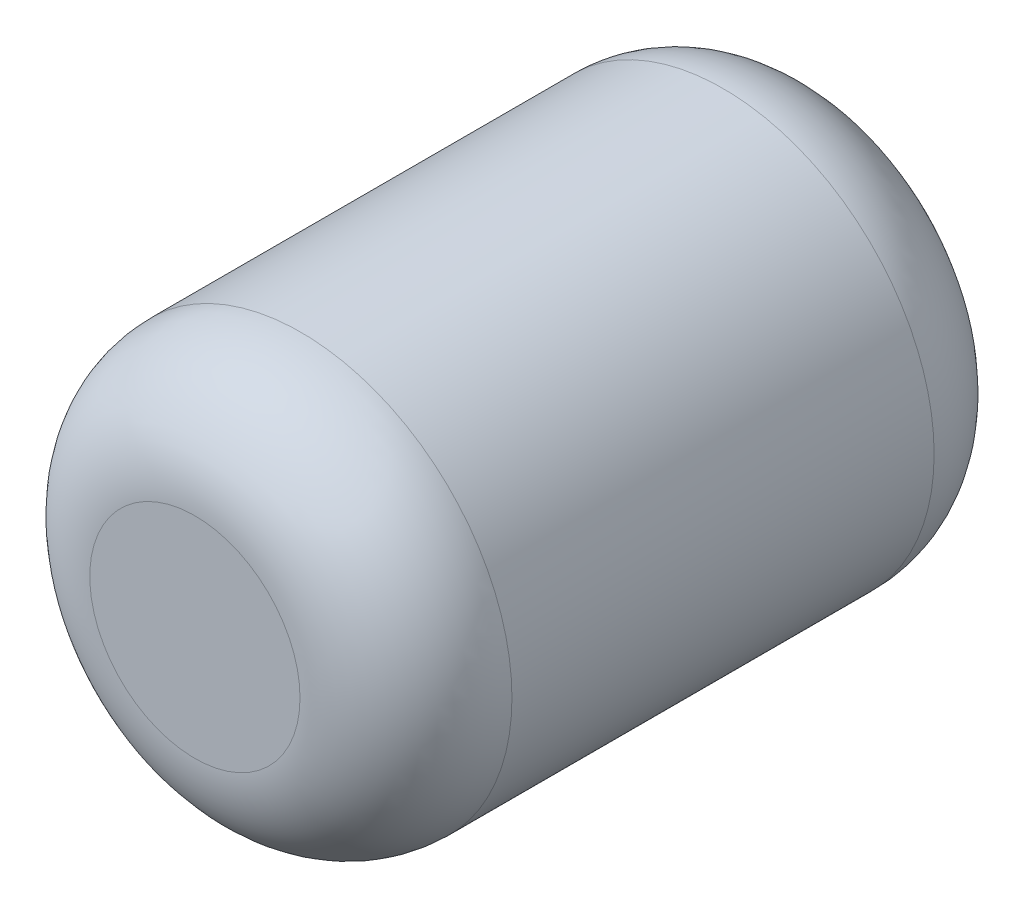
SolidWorks part; units mm, degrees
ref_plane "Plan de face" through (0, 0, 0) normal (0, 0, 1) x (1, 0, 0)
ref_plane "Plan de dessus" through (0, 0, 0) normal (0, 1, 0) x (1, 0, 0)
ref_plane "Plan de droite" through (0, 0, 0) normal (1, 0, 0) x (0, 0, -1)
sketch "Esquisse1" plane through (0, 0, 0) normal (0, 0, 1) x (1, 0, 0)
  circle A0 centre (0, 0) radius 50.5968
  dimension "D1" = 101.1936
extrude "Boss.-Extru.1" add sketch "Esquisse1" along normal blind 151.9936
fillet "Congé1" radius 25.4 2 edges at (50.5968, 0, 0) (50.5968, 0, 151.9936)
